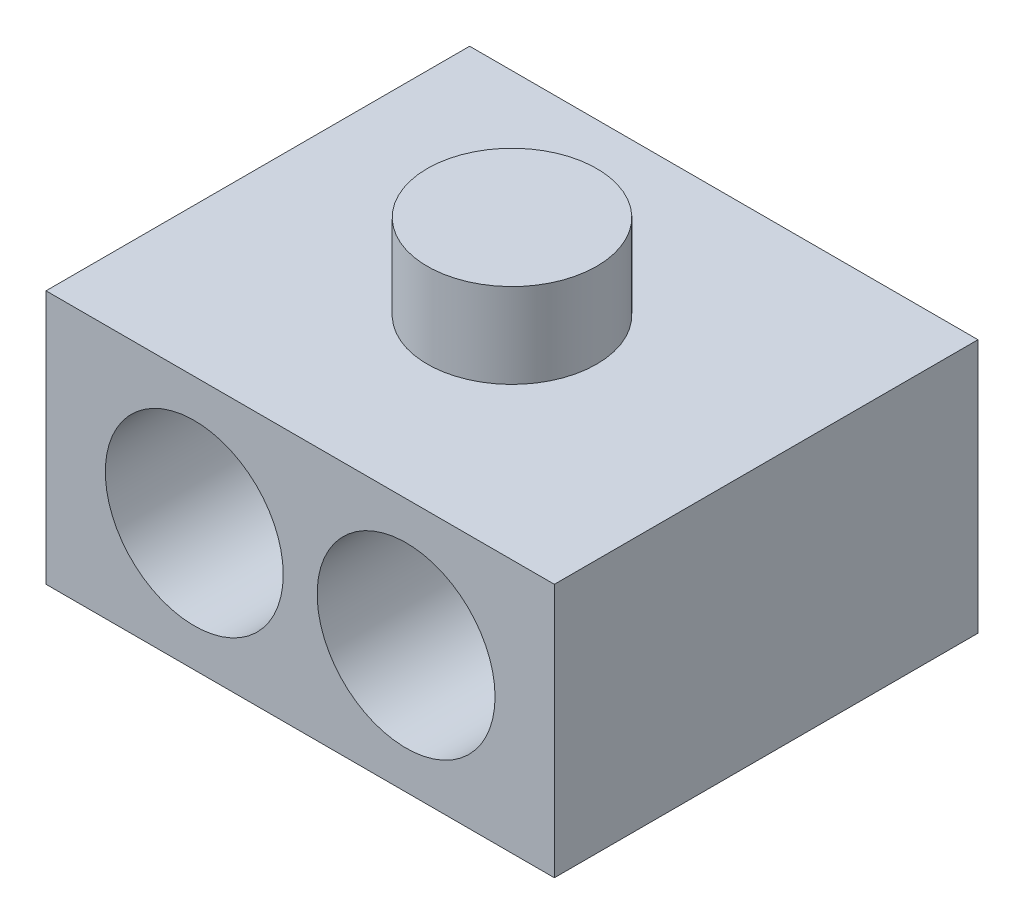
SolidWorks part; units mm, degrees
material "PVC Rigid"
ref_plane "Front Plane" through (0, 0, 0) normal (0, 0, 1) x (1, 0, 0)
ref_plane "Top Plane" through (0, 0, 0) normal (0, 1, 0) x (1, 0, 0)
ref_plane "Right Plane" through (0, 0, 0) normal (1, 0, 0) x (0, 0, -1)
sketch "Sketch1" plane through (0, 0, 0) normal (0, 0, 1) x (1, 0, 0)
  line L1 (0, 0) -> (-50, 0)
  line L2 (0, 0) -> (0, 30)
  line L3 (0, 30) -> (-50, 30)
  line L4 (-50, 0) -> (-50, 30)
  dimension "D1" = 50
  dimension "D2" = 30
extrude "Boss-Extrude1" add sketch "Sketch1" along normal blind 10
sketch "Sketch2" plane through (0, 0, 10) normal (0, 0, 1) x (1, 0, 0)
  line L0 (-50, 30) -> (-50, 0) construction
  line L1 (-50, 0) -> (0, 0) construction
  line L3 (0, 0) -> (0, 30) construction
  circle A0 centre (-37.5, 15) radius 7.5
  circle A1 centre (-12.5, 15) radius 7.5
  dimension "D1" = 12.5
  dimension "D2" = 15
  dimension "D3" = 15
  dimension "D4" = 12.5
extrude "Cut-Extrude1" cut sketch "Sketch2" against normal blind 10
sketch "Sketch3" plane through (0, 0, 10) normal (0, 0, 1) x (1, 0, 0)
  line L1 (-50, 30) -> (0, 30)
  line L2 (-50, 30) -> (-50, 0)
  line L3 (-50, 0) -> (0, 0)
  line L4 (0, 30) -> (0, 0)
extrude "Boss-Extrude2" add sketch "Sketch3" along normal blind 40
sketch "Sketch4" plane through (0, 0, 50) normal (0, 0, 1) x (1, 0, 0)
  line L0 (-50, 30) -> (-50, 0) construction
  line L1 (-50, 0) -> (0, 0) construction
  line L2 (0, 0) -> (0, 30) construction
  circle A0 centre (-37.5, 15) radius 10.5
  circle A1 centre (-12.5, 15) radius 10.5
  point P6 (0, 0)
  dimension "D1" = 12.5
  dimension "D2" = 15
  dimension "D3" = 15
  dimension "D4" = 12.5
extrude "Cut-Extrude2" cut sketch "Sketch4" against normal blind 40
sketch "Sketch5" plane through (0, 0, 0) normal (1, 0, 0) x (0, 0, -1)
  line L0 (-50, 0) -> (-50, 30) construction
  line L1 (-50, 30) -> (0, 30)
  line L2 (-50, 30) -> (-50, 0)
  line L3 (-50, 0) -> (0, 0)
  line L4 (0, 30) -> (0, 0)
extrude "Boss-Extrude3" add sketch "Sketch5" along normal blind 5
sketch "Sketch6" plane through (-50, 0, 0) normal (-1, 0, 0) x (0, 0, 1)
  line L1 (0, 0) -> (50, 0)
  line L2 (0, 0) -> (0, 30)
  line L3 (0, 30) -> (50, 30)
  line L4 (50, 0) -> (50, 30)
extrude "Boss-Extrude4" add sketch "Sketch6" along normal blind 5
sketch "Sketch7" plane through (0, 30, 0) normal (0, 1, 0) x (1, 0, 0)
  line L0 (5, 0) -> (-55, 0) construction
  line L1 (5, 0) -> (5, -50) construction
  circle A0 centre (-25, -25) radius 10
  dimension "D1" = 25
  dimension "D2" = 30
extrude "Boss-Extrude5" add sketch "Sketch7" along normal blind 10
